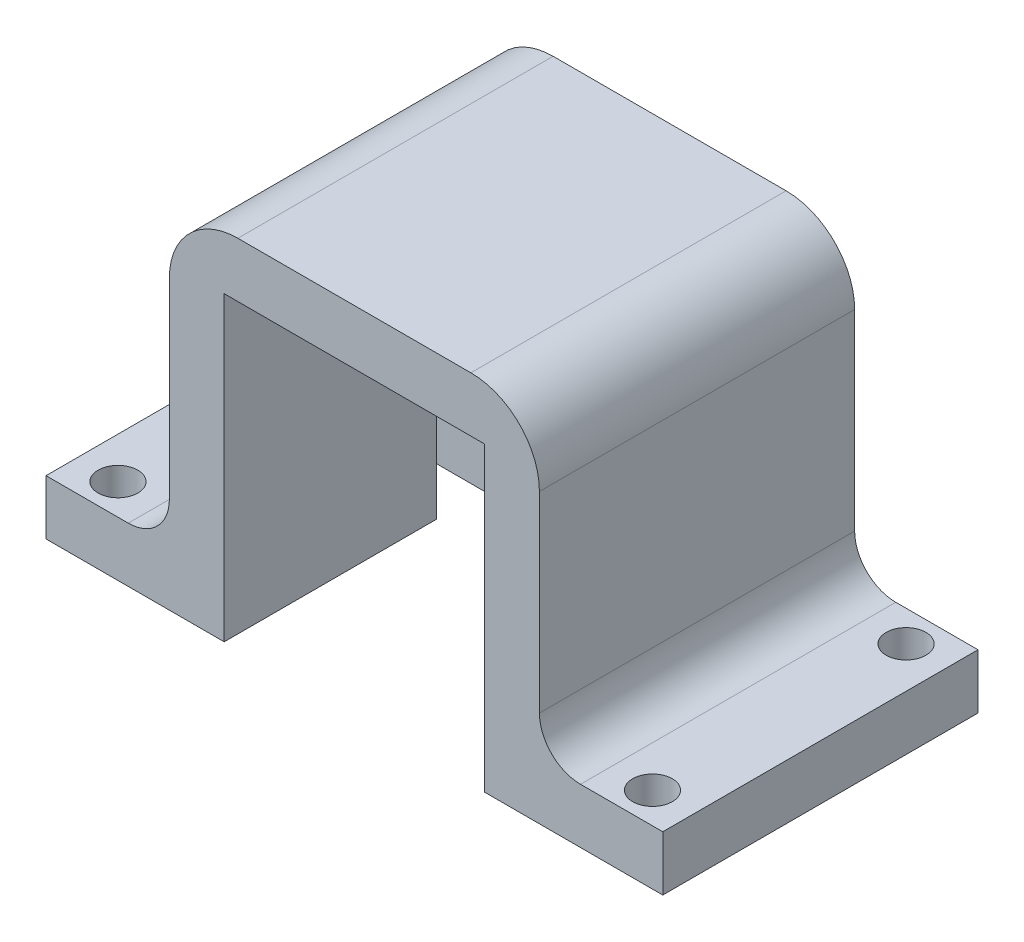
SolidWorks part; units mm, degrees
ref_plane "Front Plane" through (0, 0, 0) normal (0, 0, 1) x (1, 0, 0)
ref_plane "Top Plane" through (0, 0, 0) normal (0, 1, 0) x (1, 0, 0)
ref_plane "Right Plane" through (0, 0, 0) normal (1, 0, 0) x (0, 0, -1)
sketch "Sketch1" plane through (0, 0, 0) normal (0, 0, 1) x (1, 0, 0)
  line L0 (0, 3) -> (0, 17)
  line L1 (5, 22) -> (22, 22)
  line L2 (27, 17) -> (27, 3)
  line L3 (30, 0) -> (36, 0)
  line L4 (36, 0) -> (36, -4)
  line L5 (36, -4) -> (23, -4)
  line L6 (23, -4) -> (23, 18)
  line L7 (23, 18) -> (4, 18)
  line L8 (4, 18) -> (4, -4)
  line L9 (4, -4) -> (-9, -4)
  line L10 (-9, -4) -> (-9, 0)
  line L11 (-9, 0) -> (-3, 0)
  arc A0 (5, 22) -> (0, 17) centre (5, 17) ccw
  arc A1 (22, 22) -> (27, 17) centre (22, 17) cw
  arc A2 (0, 3) -> (-3, 0) centre (-3, 3) cw
  arc A3 (30, 0) -> (27, 3) centre (30, 3) cw
  point P3 (45.2053, -4)
  point P18 (27, 22)
  point P21 (0, 0)
  dimension "D10" = 5
  dimension "D11" = 3
  dimension "D1" = 19
  dimension "D2" = 4
  dimension "D3" = 4
  dimension "D4" = 4
  dimension "D5" = 4
  dimension "D6" = 4
  dimension "D7" = 22
  dimension "D8" = 13
  dimension "D9" = 13
extrude "Boss-Extrude1" add sketch "Sketch1" along normal blind 23
ref_plane "Plane1" through (13.5, 0, 0) normal (1, 0, 0) x (0, 0, -1)
sketch "Sketch3" plane through (0, 0, 0) normal (0, 1, 0) x (1, 0, 0)
  line L0 (-9, -11.5) -> (36, -11.5) construction
  line L1 (-9, -23) -> (-9, 0) construction
  line L2 (36, -23) -> (36, 0) construction
  line L3 (13.5, -12.1) -> (13.5, 12.1) construction
  line L4 (36, 0) -> (30, 0) construction
  line L6 (36, -23) -> (30, -23) construction
  circle A0 centre (-6, -2.25) radius 1.45
  circle A1 centre (-6, -20.75) radius 1.45
  circle A2 centre (33, -20.75) radius 1.45
  circle A3 centre (33, -2.25) radius 1.45
  point P16 (0, 0)
  point P17 (0, 0)
  point P18 (0, 0)
  point P23 (33, -23)
  point P25 (0, 0)
  point P26 (0, 0)
  dimension "D1" = 2.9
  dimension "D2" = 2.25
  dimension "D3" = 2.25
extrude "Cut-Extrude1" cut sketch "Sketch3" against normal blind 23 contours A3 | A2 | A1 | A0
sketch "Sketch4" plane through (0, 0, 0) normal (-1, 0, 0) x (0, 0, 1)
  line L0 (23, 17) -> (0, 17) construction
  line L1 (4, 17) -> (7.5, 17)
  line L2 (4, 17) -> (4, -4)
  line L3 (4, -4) -> (7.5, -4)
  line L4 (7.5, 17) -> (7.5, -4)
  line L5 (23, -4) -> (0, -4) construction
  line L7 (0, 0) -> (0, -4) construction
  dimension "D1" = 4
  dimension "D2" = 3.5
extrude "Cut-Extrude2" cut sketch "Sketch4" against normal blind 10 and the other way blind 23
